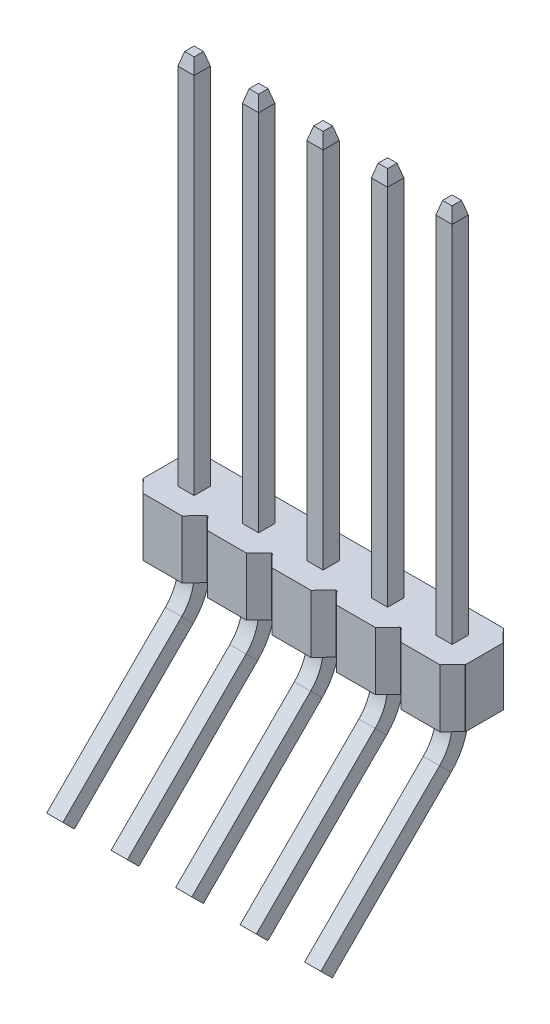
SolidWorks part; units mm, degrees
ref_plane "Front Plane" through (0, 0, 0) normal (0, 0, 1) x (1, 0, 0)
ref_plane "Top Plane" through (0, 0, 0) normal (0, 1, 0) x (1, 0, 0)
ref_plane "Right Plane" through (0, 0, 0) normal (1, 0, 0) x (0, 0, -1)
sketch "Sketch1" plane through (0, 0, 0) normal (0, 1, 0) x (1, 0, 0)
  line L14 (-0.77, 1.25) -> (0.77, 1.25)
  line L20 (-0.77, -1.25) -> (0.77, -1.25)
  line L22 (1.27, -0.75) -> (1.27, 0.75)
  line L23 (1.27, -1.25) -> (-1.27, 1.25) construction
  line L24 (0.77, -1.25) -> (1.25, -0.75)
  line L25 (1.25, -0.75) -> (1.27, -0.75)
  line L26 (0, 0) -> (0, -1.4708) construction
  line L27 (0, 0) -> (1.4893, 0) construction
  line L28 (0.77, 1.25) -> (1.25, 0.75)
  line L29 (1.25, 0.75) -> (1.27, 0.75)
  line L30 (-1.25, 0.75) -> (-1.27, 0.75)
  line L31 (-0.77, 1.25) -> (-1.25, 0.75)
  line L32 (-1.25, -0.75) -> (-1.27, -0.75)
  line L33 (-0.77, -1.25) -> (-1.25, -0.75)
  line L34 (-1.27, -0.75) -> (-1.27, 0.75)
  point P25 (0, 1.25)
  point P29 (0, 0)
  point P38 (1.27, 0)
  point P43 (0, -1.25)
  dimension "D11" = 1.25
  dimension "D12" = 1.27
  dimension "D13" = 0.5
  dimension "D14" = 0.02
  dimension "D15" = 0.5
extrude "Boss-Extrude1" add sketch "Sketch1" along normal blind 2.29
sketch "Sketch2" plane through (0, 0, 0) normal (1, 0, 0) x (0, 0, -1)
  line L0 (0, 17.12) -> (0, -0.4081)
  line L2 (-0.5858, -1.8224) -> (-5.2634, -6.5)
  line L3 (0.75, 0) -> (1.25, 0) construction
  arc A0 (0, -0.4081) -> (-0.5858, -1.8224) centre (-2, -0.4081) cw
  dimension "D4" = 2
  dimension "D1" = 23.62
  dimension "D2" = 135
  dimension "D3" = 6.5
ref_plane "Plane1" through (0, 17.12, 0) normal (0, 1, 0) x (1, 0, 0)
sketch "Sketch3" plane through (0, 17.12, 0) normal (0, 1, 0) x (1, 0, 0)
  line L1 (-0.32, 0.32) -> (0.32, 0.32)
  line L2 (-0.32, 0.32) -> (-0.32, -0.32)
  line L3 (-0.32, -0.32) -> (0.32, -0.32)
  line L4 (0.32, 0.32) -> (0.32, -0.32)
  line L5 (-0.32, 0.32) -> (0.32, -0.32) construction
  line L6 (-0.32, -0.32) -> (0.32, 0.32) construction
  point P0 (0, 0)
  dimension "D1" = 0.64
sweep "Sweep1" add profiles "Sketch3" path "Sketch2"
chamfer "Chamfer3" distance 0.5 angle 15 4 edges at (0, 17.12, 0.32) (-0.32, 17.12, 0) (0, 17.12, -0.32) (0.32, 17.12, 0)
pattern_linear "LPattern1" count 5 spacing 2.54 along (1, 0, 0) of "Boss-Extrude1", "Chamfer3", "Sweep1"
